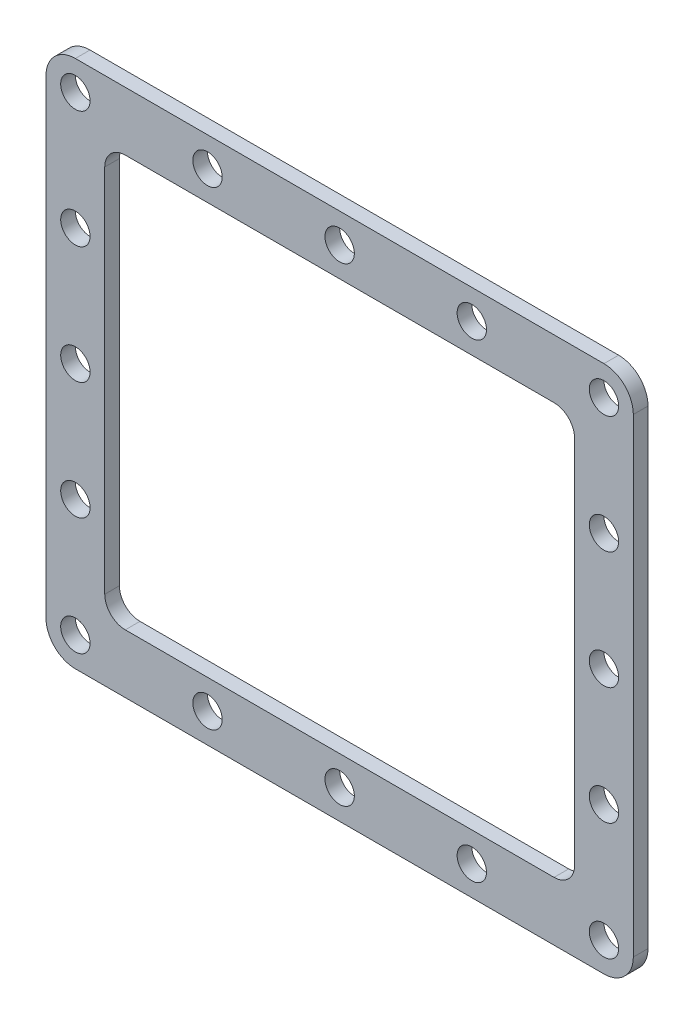
SolidWorks part; units mm, degrees
ref_plane "前视基准面" through (0, 0, 0) normal (0, 0, 1) x (1, 0, 0)
ref_plane "上视基准面" through (0, 0, 0) normal (0, 1, 0) x (1, 0, 0)
ref_plane "右视基准面" through (0, 0, 0) normal (1, 0, 0) x (0, 0, -1)
sketch "草图1" plane through (0, 0, 0) normal (0, 0, 1) x (1, 0, 0)
  line L0 (90, -80) -> (90, 80) construction
  line L1 (-90, -90) -> (90, -90)
  line L2 (-100, -80) -> (-100, 80)
  line L3 (-90, 90) -> (90, 90)
  line L4 (100, -80) -> (100, 80)
  line L5 (-100, -90) -> (100, 90) construction
  line L6 (-100, 90) -> (100, -90) construction
  line L7 (-73, -70) -> (73, -70)
  line L8 (-80, -63) -> (-80, 63)
  line L9 (-73, 70) -> (73, 70)
  line L10 (80, -63) -> (80, 63)
  line L11 (-80, -70) -> (80, 70) construction
  line L12 (-80, 70) -> (80, -70) construction
  line L13 (0, 0) -> (0, 37.6622) construction
  line L14 (0, 0) -> (41.7484, 0) construction
  line L15 (-90, 80) -> (90, 80) construction
  line L16 (-90, -80) -> (90, -80) construction
  arc A0 (90, 90) -> (100, 80) centre (90, 80) cw
  arc A1 (90, -90) -> (100, -80) centre (90, -80) ccw
  arc A2 (-90, -90) -> (-100, -80) centre (-90, -80) cw
  arc A3 (-100, 80) -> (-90, 90) centre (-90, 80) cw
  arc A4 (73, 70) -> (80, 63) centre (73, 63) cw
  arc A5 (73, -70) -> (80, -63) centre (73, -63) ccw
  arc A6 (-73, -70) -> (-80, -63) centre (-73, -63) cw
  arc A7 (-80, 63) -> (-73, 70) centre (-73, 63) cw
  circle A8 centre (90, -80) radius 5
  circle A9 centre (90, 80) radius 5
  circle A10 centre (-90, 80) radius 5
  circle A11 centre (-90, -80) radius 5
  circle A12 centre (90, 0) radius 5
  circle A13 centre (90, -40) radius 5
  circle A14 centre (90, 40) radius 5
  circle A15 centre (-90, -40) radius 5
  circle A16 centre (-90, 0) radius 5
  circle A17 centre (-90, 40) radius 5
  circle A18 centre (0, 80) radius 5
  circle A19 centre (-45, 80) radius 5
  circle A20 centre (45, 80) radius 5
  circle A21 centre (0, -80) radius 5
  circle A22 centre (-45, -80) radius 5
  circle A23 centre (45, -80) radius 5
  point P0 (0, 0)
  point P17 (0, 0)
  dimension "D3" = 10
  dimension "D6" = 7
  dimension "D7" = 10
  dimension "D8" = 10
  dimension "D9" = 10
  dimension "D10" = 10
  dimension "D11" = 10
  dimension "D12" = 10
  dimension "D13" = 10
  dimension "D16" = 10
  dimension "D17" = 10
  dimension "D18" = 10
  dimension "D21" = 10
  dimension "D22" = 10
  dimension "D25" = 10
  dimension "D1" = 180
  dimension "D2" = 200
  dimension "D4" = 20
  dimension "D5" = 20
  dimension "D14" = 40
  dimension "D15" = 40
  dimension "D19" = 45
  dimension "D20" = 45
  dimension "D23" = 45
  dimension "D24" = 45
extrude "凸台-拉伸1" add sketch "草图1" along normal blind 5
